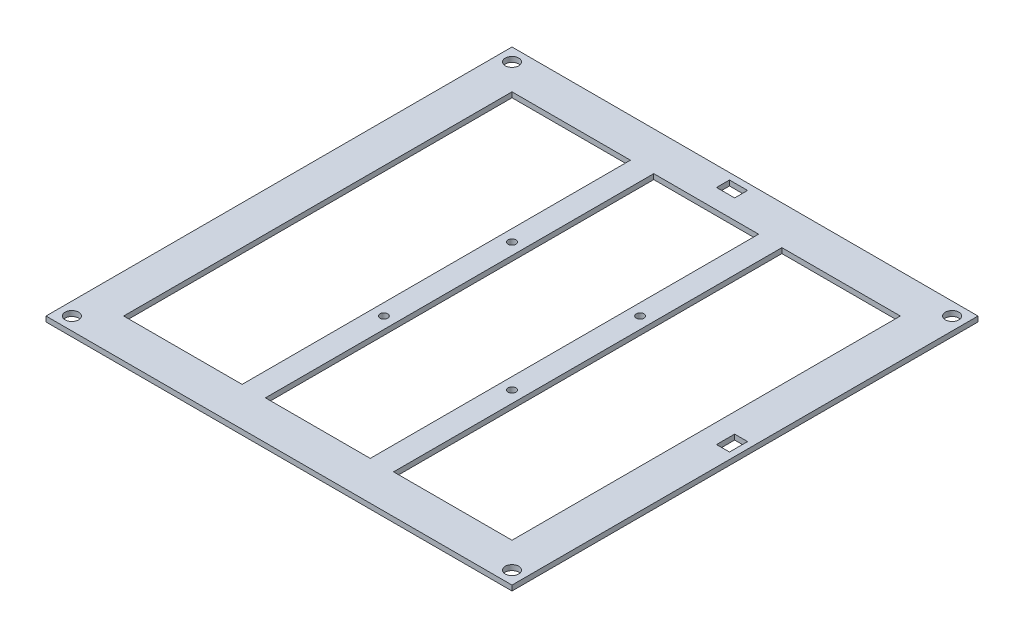
SolidWorks part; units mm, degrees
ref_plane "Alzado" through (0, 0, 0) normal (0, 0, 1) x (1, 0, 0)
ref_plane "Planta" through (0, 0, 0) normal (0, 1, 0) x (1, 0, 0)
ref_plane "Vista lateral" through (0, 0, 0) normal (1, 0, 0) x (0, 0, -1)
sketch "Croquis1" plane through (0, 0, 0) normal (0, 1, 0) x (1, 0, 0)
  line L0 (-10, -10) -> (-10, 180)
  line L1 (0, 0) -> (170, 0) construction
  line L2 (0, 0) -> (0, 170) construction
  line L3 (0, 170) -> (170, 170) construction
  line L4 (170, 0) -> (170, 170) construction
  line L5 (-10, 180) -> (180, 180)
  line L6 (180, -10) -> (180, 180)
  line L7 (-10, -10) -> (180, -10)
  line L8 (10, 10) -> (10, 160)
  line L9 (10, 160) -> (55.75, 160)
  line L10 (160, 10) -> (160, 160)
  line L11 (10, 10) -> (55.75, 10)
  line L12 (10, 85) -> (160, 85) construction
  line L13 (60.25, 85) -> (60.25, 109.75) construction
  line L14 (60.25, 85) -> (60.25, 60.25) construction
  line L15 (85, 85) -> (85, 160) construction
  line L16 (55.75, 147.7957) -> (64.75, 147.7957) construction
  line L18 (55.75, 160) -> (55.75, 10)
  line L20 (64.75, 160) -> (64.75, 10)
  line L21 (60.25, 147.7957) -> (60.25, 109.75) construction
  line L22 (64.75, 160) -> (105.25, 160)
  line L23 (64.75, 10) -> (105.25, 10)
  line L24 (10, 160) -> (160, 160) construction
  line L25 (105.25, 160) -> (105.25, 10)
  line L26 (10, 10) -> (160, 10) construction
  line L27 (114.25, 160) -> (114.25, 10)
  line L28 (114.25, 160) -> (160, 160)
  line L29 (114.25, 10) -> (160, 10)
  line L31 (167.5, 81.5) -> (172.5, 81.5)
  line L32 (167.5, 81.5) -> (167.5, 88.5)
  line L33 (167.5, 88.5) -> (172.5, 88.5)
  line L34 (172.5, 81.5) -> (172.5, 88.5)
  line L35 (167.5, 81.5) -> (172.5, 88.5) construction
  line L36 (167.5, 88.5) -> (172.5, 81.5) construction
  line L37 (81.5, 172.5) -> (88.5, 172.5)
  line L38 (81.5, 172.5) -> (81.5, 167.5)
  line L39 (81.5, 167.5) -> (88.5, 167.5)
  line L40 (88.5, 172.5) -> (88.5, 167.5)
  line L41 (81.5, 172.5) -> (88.5, 167.5) construction
  line L42 (81.5, 167.5) -> (88.5, 172.5) construction
  circle A0 centre (60.25, 109.75) radius 1.5
  circle A1 centre (60.25, 60.25) radius 1.5
  circle A2 centre (0, 170) radius 2.6
  circle A3 centre (0, 0) radius 2.6
  circle A4 centre (109.75, 109.75) radius 1.5
  circle A5 centre (109.75, 60.25) radius 1.5
  circle A6 centre (170, 0) radius 2.6
  circle A7 centre (170, 170) radius 2.6
  point P41 (170, 85)
  point P46 (85, 170)
  dimension "D4" = 3
  dimension "D8" = 5.2
  dimension "D1" = 170
  dimension "D2" = 10
  dimension "D5" = 24.75
  dimension "D6" = 24.75
  dimension "D7" = 9
  dimension "D9" = 5
  dimension "D10" = 7
  dimension "D3" = 10
extrude "Saliente-Extruir1" add sketch "Croquis1" along normal blind 2
sketch "Croquis2" plane through (0, 2, 0) normal (0, 1, 0) x (1, 0, 0)
  line L0 (-5, -5) -> (175, -5)
  line L1 (175, -5) -> (175, 175)
  line L2 (175, 175) -> (-5, 175)
  line L3 (-5, 175) -> (-5, -5)
  line L4 (-10, -10) -> (180, -10)
  line L5 (180, -10) -> (180, 180)
  line L6 (180, 180) -> (-10, 180)
  line L7 (-10, 180) -> (-10, -10)
  line L8 (-10, -10) -> (180, -10)
  line L9 (180, -10) -> (180, 180)
  line L10 (180, 180) -> (-10, 180)
  line L11 (-10, 180) -> (-10, -10)
  dimension "D1" = 0
  dimension "D2" = 5
extrude "Cortar-Extruir1" cut sketch "Croquis2" against normal blind 74
